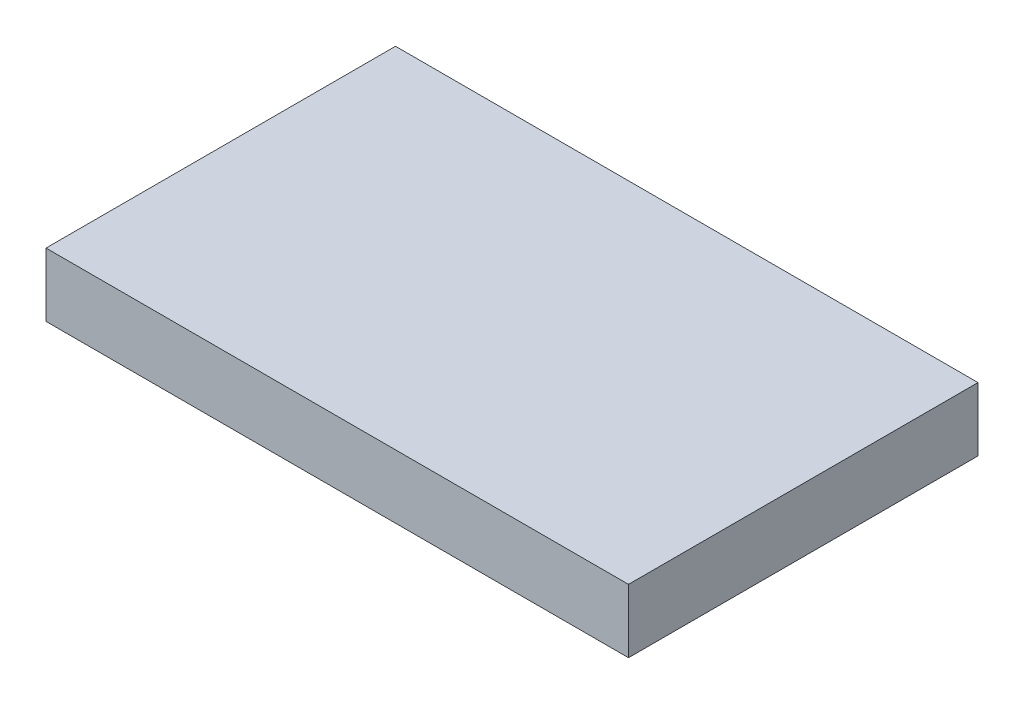
SolidWorks part; units mm, degrees
ref_plane "前视基准面" through (0, 0, 0) normal (0, 0, 1) x (1, 0, 0)
ref_plane "上视基准面" through (0, 0, 0) normal (0, 1, 0) x (1, 0, 0)
ref_plane "右视基准面" through (0, 0, 0) normal (1, 0, 0) x (0, 0, -1)
other "Configuration Table"
sketch "草图1" plane through (0, 0, 0) normal (0, 1, 0) x (1, 0, 0)
  line L1 (-13.75, -8.25) -> (13.75, -8.25)
  line L2 (-13.75, -8.25) -> (-13.75, 8.25)
  line L3 (-13.75, 8.25) -> (13.75, 8.25)
  line L4 (13.75, -8.25) -> (13.75, 8.25)
  line L5 (-13.75, -8.25) -> (13.75, 8.25) construction
  line L6 (-13.75, 8.25) -> (13.75, -8.25) construction
  point P0 (0, 0)
  dimension "D1" = 16.5
  dimension "D2" = 27.5
extrude "凸台-拉伸1" add sketch "草图1" along normal blind 3
